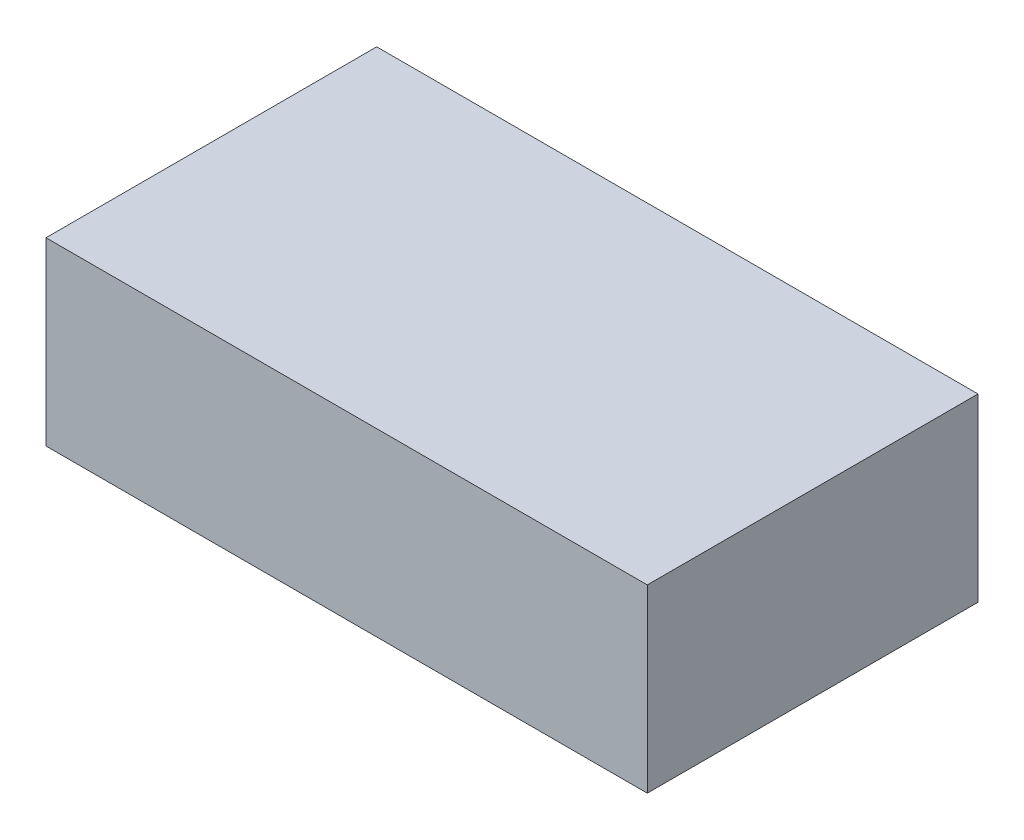
SolidWorks part; units mm, degrees
ref_plane "Front Plane" through (0, 0, 0) normal (0, 0, 1) x (1, 0, 0)
ref_plane "Top Plane" through (0, 0, 0) normal (0, 1, 0) x (1, 0, 0)
ref_plane "Right Plane" through (0, 0, 0) normal (1, 0, 0) x (0, 0, -1)
sketch "Sketch1" plane through (0, 0, 0) normal (0, 1, 0) x (1, 0, 0)
  line L1 (-31.75, -17.4625) -> (31.75, -17.4625)
  line L2 (-31.75, -17.4625) -> (-31.75, 17.4625)
  line L3 (-31.75, 17.4625) -> (31.75, 17.4625)
  line L4 (31.75, -17.4625) -> (31.75, 17.4625)
  line L5 (-31.75, -17.4625) -> (31.75, 17.4625) construction
  line L6 (-31.75, 17.4625) -> (31.75, -17.4625) construction
  point P0 (0, 0)
  dimension "D1" = 63.5
  dimension "D2" = 34.925
extrude "Boss-Extrude1" add sketch "Sketch1" along normal blind 19.05
